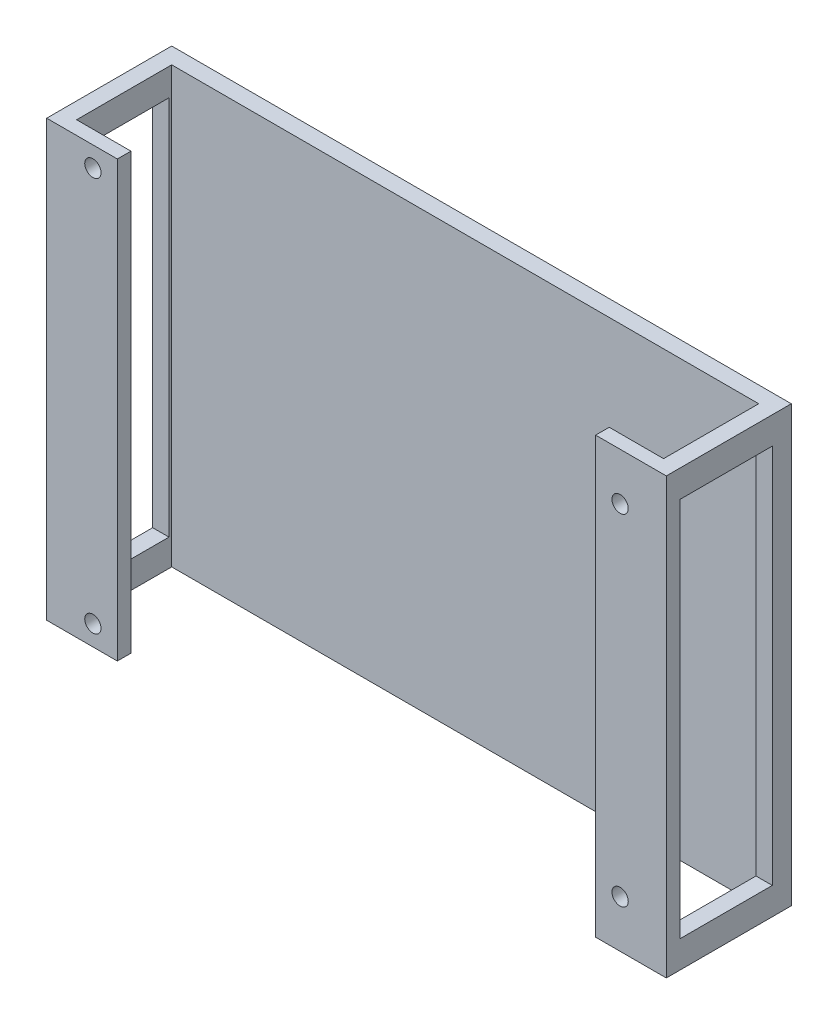
SolidWorks part; units mm, degrees
ref_plane "Front Plane" through (0, 0, 0) normal (0, 0, 1) x (1, 0, 0)
ref_plane "Top Plane" through (0, 0, 0) normal (0, 1, 0) x (1, 0, 0)
ref_plane "Right Plane" through (0, 0, 0) normal (1, 0, 0) x (0, 0, -1)
sketch "Sketch10" plane through (0, 0, 0) normal (0, 0, 1) x (1, 0, 0)
  line L0 (23.9262, 27.4356) -> (72.4262, -3.8594) construction
  line L2 (-33.0738, 67.4356) -> (80.9262, 67.4356)
  line L3 (-33.0738, 67.4356) -> (-33.0738, -12.5644)
  line L4 (-33.0738, -12.5644) -> (80.9262, -12.5644)
  line L5 (80.9262, 67.4356) -> (80.9262, -12.5644)
  point P8 (48.1762, 11.7881)
  point P13 (0, 0)
  point P14 (0, 0)
  dimension "D8" = 114
  dimension "D9" = 80
extrude "Boss-Extrude6" add sketch "Sketch10" along normal blind 3
sketch "Sketch12" plane through (0, 0, 3) normal (0, 0, 1) x (1, 0, 0)
  line L0 (-33.0738, 67.4356) -> (-30.0738, 67.4356)
  line L1 (80.9262, 67.4356) -> (-33.0738, 67.4356) construction
  line L2 (-30.0738, 67.4356) -> (-30.0738, -12.5644)
  line L3 (-33.0738, -12.5644) -> (80.9262, -12.5644) construction
  line L4 (-30.0738, -12.5644) -> (-33.0738, -12.5644)
  line L5 (-33.0738, -12.5644) -> (-33.0738, 67.4356)
  dimension "D1" = 3
extrude "Boss-Extrude7" add sketch "Sketch12" along normal blind 20 contours L5 L0 L2 L4
sketch "Sketch13" plane through (-30.0738, 0, 0) normal (1, 0, 0) x (0, 0, -1)
  line L0 (-23, 67.4356) -> (-20.5, 67.4356)
  line L1 (-23, 67.4356) -> (-3, 67.4356) construction
  line L2 (-20.5, 67.4356) -> (-20.5, -12.5644)
  line L3 (-23, -12.5644) -> (-3, -12.5644) construction
  line L4 (-20.5, -12.5644) -> (-23, -12.5644)
  line L5 (-23, -12.5644) -> (-23, 67.4356)
  dimension "D1" = 2.5
extrude "Boss-Extrude8" add sketch "Sketch13" along normal blind 10
ref_plane "Plane2" through (23.9262, 0, 0) normal (-1, 0, 0) x (0, 0, 1)
ref_plane "Plane3" through (25.4262, 0, 0) normal (-1, 0, 0) x (0, 0, 1)
mirror "Mirror3" about plane through (23.9262, 0, 0) normal (-1, 0, 0) of "Boss-Extrude6", "Boss-Extrude7", "Boss-Extrude8"
sketch "Sketch16" plane through (-33.0738, 0, 0) normal (-1, 0, 0) x (0, 0, 1)
  line L0 (23, 67.4356) -> (0, -12.5644) construction
  line L1 (0, 67.4356) -> (23, -12.5644) construction
  line L3 (3.5, 62.4356) -> (19.5, 62.4356)
  line L4 (3.5, 62.4356) -> (3.5, -7.5644)
  line L5 (3.5, -7.5644) -> (19.5, -7.5644)
  line L6 (19.5, 62.4356) -> (19.5, -7.5644)
  line L7 (3.5, 62.4356) -> (19.5, -7.5644) construction
  line L8 (3.5, -7.5644) -> (19.5, 62.4356) construction
  point P8 (11.5, 27.4356)
  dimension "D1" = 16
  dimension "D2" = 70
extrude "Cut-Extrude3" cut sketch "Sketch16" against normal through all
sketch "Sketch18" plane through (0, 0, 23) normal (0, 0, 1) x (1, 0, 0)
  circle A0 centre (-24.5738, 63.7286) radius 1.5 construction
  circle A1 centre (-24.5738, -8.8575) radius 1.5 construction
  circle A2 centre (72.4262, 58.7286) radius 1.5 construction
  circle A3 centre (72.4262, -3.8575) radius 1.5 construction
  circle A4 centre (-24.5738, 63.7286) radius 1.5
  circle A5 centre (-24.5738, -8.8575) radius 1.5
  circle A6 centre (72.4262, 58.7286) radius 1.5
  circle A7 centre (72.4262, -3.8575) radius 1.5
extrude "Cut-Extrude4" cut sketch "Sketch18" against normal blind 10
sketch "Sketch19" plane through (77.9262, 0, 0) normal (-1, 0, 0) x (0, 0, 1)
  line L8 (19.5, 62.4356) -> (19.5, -7.5644)
  line L9 (19.5, 62.4356) -> (20.5, 62.4356)
  line L10 (20.5, -12.5644) -> (20.5, 67.4356) construction
  line L12 (19.5, -7.5644) -> (20.5, -7.5644)
  line L13 (20.5, -7.5644) -> (20.5, 62.4356)
extrude "Cut-Extrude5" cut sketch "Sketch19" against normal through all both and the other way through all
